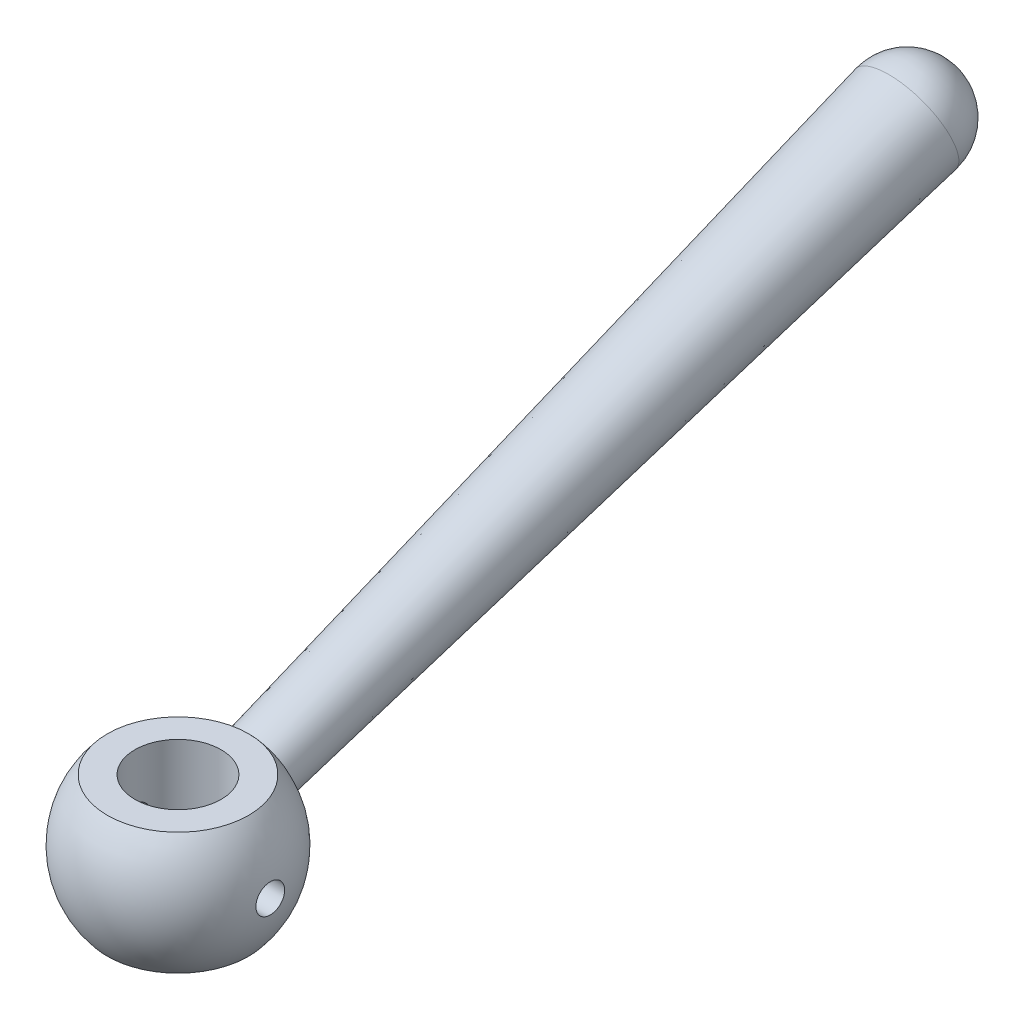
SolidWorks part; units mm, degrees
ref_plane "前视基准面" through (0, 0, 0) normal (0, 0, 1) x (1, 0, 0)
ref_plane "上视基准面" through (0, 0, 0) normal (0, 1, 0) x (1, 0, 0)
ref_plane "右视基准面" through (0, 0, 0) normal (1, 0, 0) x (0, 0, -1)
sketch "草图1" plane through (0, 0, 0) normal (1, 0, 0) x (0, 0, -1)
  line L0 (0, 13) -> (0, -13)
  line L1 (0, -13) -> (0, -30.5168) construction
  arc A0 (0, -13) -> (0, 13) centre (0, 0) ccw
  dimension "D1" = 26
revolve "旋转1" add sketch "草图1" angle 360 about L1
sketch "草图2" plane through (0, 0, 0) normal (1, 0, 0) x (0, 0, -1)
  line L1 (-13, -8.5) -> (13, -8.5)
  line L2 (-13, -8.5) -> (-13, 8.5)
  line L3 (-13, 8.5) -> (13, 8.5)
  line L4 (13, -8.5) -> (13, 8.5)
  line L5 (-13, -8.5) -> (13, 8.5) construction
  line L6 (-13, 8.5) -> (13, -8.5) construction
  circle A1 centre (0, 0) radius 13 construction
  point P0 (0, 0)
  dimension "D1" = 17
extrude "切除-拉伸1" cut sketch "草图2" against normal through all both and the other way through all flip side to cut
sketch "草图3" plane through (0, 8.5, 0) normal (0, 1, 0) x (1, 0, 0)
  circle A0 centre (0, 0) radius 6
  dimension "D1" = 12
extrude "切除-拉伸2" cut sketch "草图3" against normal through all both and the other way through all
sketch "草图4" plane through (0, 0, 0) normal (1, 0, 0) x (0, 0, -1)
  circle A0 centre (0, 0) radius 2
  dimension "D1" = 4
extrude "切除-拉伸3" cut sketch "草图4" against normal through all both and the other way through all
sketch "草图5" plane through (0, 0, 0) normal (1, 0, 0) x (0, 0, -1)
  line L0 (11.4629, 4.1722) -> (101.4868, 36.9382) construction
  line L1 (11.4629, 4.1722) -> (5.969, 2.1726) construction
  line L2 (9.926, 8.3949) -> (98.9213, 43.4511)
  line L4 (9.926, 8.3949) -> (11.4629, 4.1722)
  line L5 (11.4629, 4.1722) -> (108.0647, 39.3323)
  arc A0 (13, 0) -> (9.8362, 8.5) centre (0, 0) ccw construction
  arc A1 (108.0647, 39.3323) -> (98.9213, 43.4511) centre (101.4868, 36.9382) ccw
  point P11 (12.216, 4.4463)
  point P12 (11.4629, 4.1722)
  dimension "D4" = 14
  dimension "D3" = 95
revolve "旋转2" add sketch "草图5" angle 360 about L1
